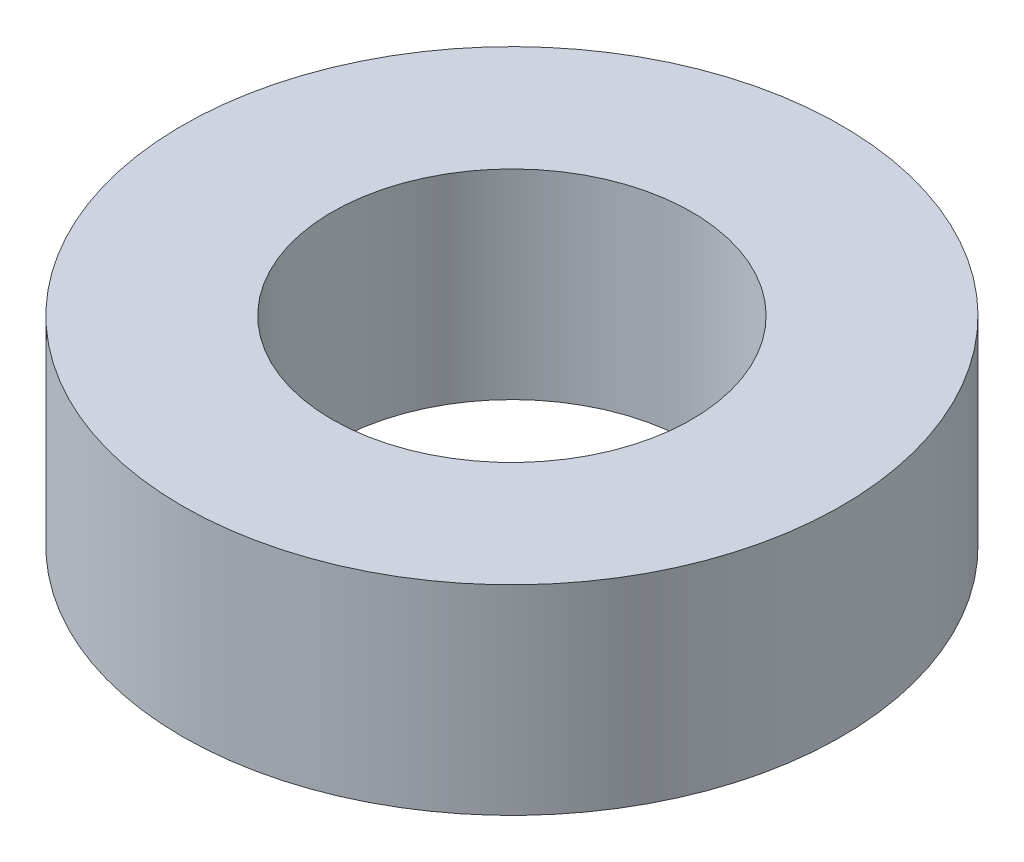
SolidWorks part; units mm, degrees
ref_plane "Front Plane" through (0, 0, 0) normal (0, 0, 1) x (1, 0, 0)
ref_plane "Top Plane" through (0, 0, 0) normal (0, 1, 0) x (1, 0, 0)
ref_plane "Right Plane" through (0, 0, 0) normal (1, 0, 0) x (0, 0, -1)
sketch "Sketch1" plane through (0, 0, 0) normal (0, 1, 0) x (1, 0, 0)
  circle A0 centre (0, 0) radius 1.8
  circle A1 centre (0, 0) radius 3.3
  dimension "D1" = 3.6
  dimension "D2" = 1.5
extrude "Boss-Extrude1" add sketch "Sketch1" along normal blind 2
